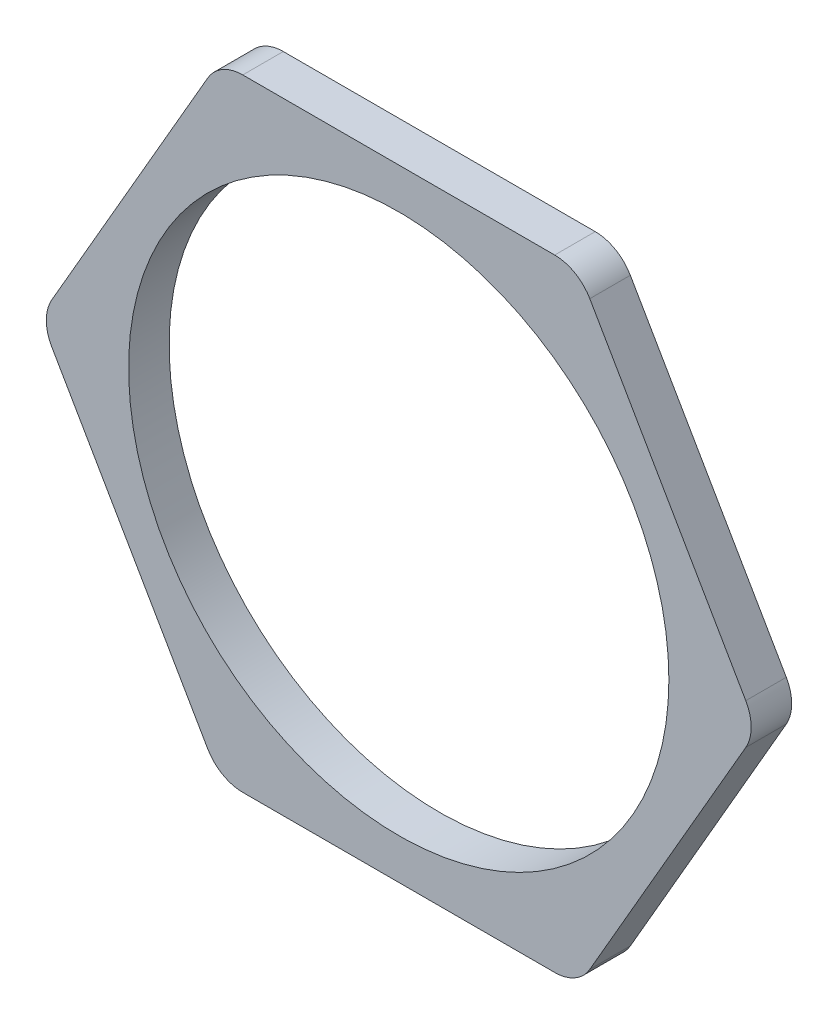
SolidWorks part; units mm, degrees
ref_plane "Front Plane" through (0, 0, 0) normal (0, 0, 1) x (1, 0, 0)
ref_plane "Top Plane" through (0, 0, 0) normal (0, 1, 0) x (1, 0, 0)
ref_plane "Right Plane" through (0, 0, 0) normal (1, 0, 0) x (0, 0, -1)
sketch "Sketch1" plane through (0, 0, 0) normal (0, 0, 1) x (1, 0, 0)
  line L0 (0, 0) -> (-67.2918, 0) construction
  line L1 (0, 0) -> (0, -56.0765) construction
  line L2 (-13.2791, 23) -> (-26.5581, 0)
  line L3 (0, 0) -> (-19.9186, 11.5) construction
  line L4 (-13.2791, -23) -> (-26.5581, 0)
  line L5 (-13.2791, -23) -> (13.2791, -23)
  line L6 (-13.2791, 23) -> (13.2791, 23)
  line L7 (13.2791, -23) -> (26.5581, 0)
  line L8 (13.2791, 23) -> (26.5581, 0)
  circle A0 centre (0, 0) radius 20
  point P13 (0, -23)
  point P15 (0, 23)
extrude "Boss-Extrude1" add sketch "Sketch1" along normal blind 3
fillet "Fillet4" radius 3 6 edges at (-13.2791, 23, 1.5) (-26.5581, 0, 1.5) (-13.2791, -23, 1.5) (13.2791, -23, 1.5) (26.5581, 0, 1.5) (13.2791, 23, 1.5)
